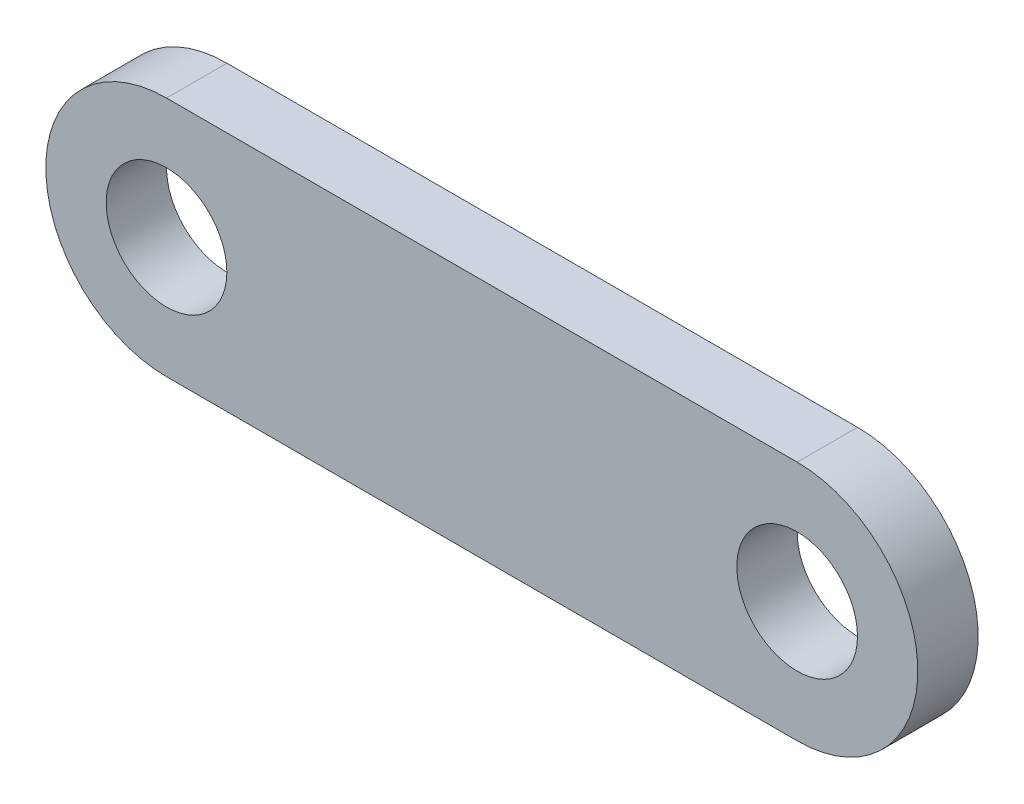
SolidWorks part; units mm, degrees
ref_plane "Plano frontal" through (0, 0, 0) normal (0, 0, 1) x (1, 0, 0)
ref_plane "Plano superior" through (0, 0, 0) normal (0, 1, 0) x (1, 0, 0)
ref_plane "Plano direito" through (0, 0, 0) normal (1, 0, 0) x (0, 0, -1)
sketch "Esboço1" plane through (0, 0, 0) normal (0, 0, 1) x (1, 0, 0)
  line L0 (-5.225, 2) -> (5.225, 2)
  line L1 (-5.225, 0) -> (5.225, 0) construction
  line L2 (-5.225, -2) -> (5.225, -2)
  arc A0 (-5.225, 2) -> (-5.225, -2) centre (-5.225, 0) ccw
  arc A1 (5.225, 2) -> (5.225, -2) centre (5.225, 0) cw
  circle A2 centre (-5.225, 0) radius 1
  circle A3 centre (5.225, 0) radius 1
  point P3 (0, 2)
  dimension "D1" = 10.45
  dimension "D2" = 2
extrude "Ressalto-extrusão1" add sketch "Esboço1" along normal blind 1
